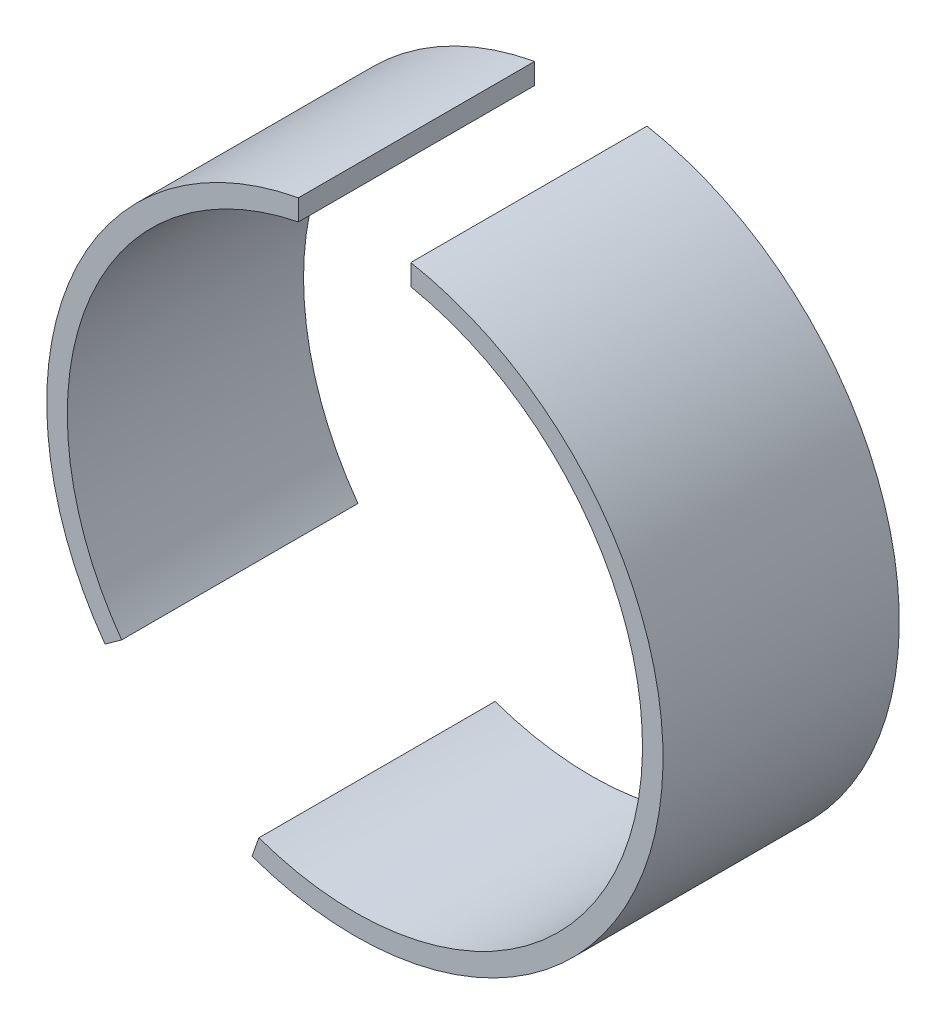
SolidWorks part; units mm, degrees
ref_plane "Front Plane" through (0, 0, 0) normal (0, 0, 1) x (1, 0, 0)
ref_plane "Top Plane" through (0, 0, 0) normal (0, 1, 0) x (1, 0, 0)
ref_plane "Right Plane" through (0, 0, 0) normal (1, 0, 0) x (0, 0, -1)
sketch "Sketch2" plane through (0, 0, 0) normal (0, 0, 1) x (1, 0, 0)
  line L0 (-9.3464, -26.394) -> (-10.014, -28.2793)
  line L1 (5.44, 27.4665) -> (5.44, 29.5027)
  line L7 (-24.3262, -17.5566) -> (-22.7045, -16.3862)
  line L8 (-5.5, 29.4915) -> (-5.5, 27.4545)
  arc A2 (-9.3464, -26.394) -> (5.44, 27.4665) centre (0, 0) ccw
  arc A5 (-5.5, 27.4545) -> (-22.7045, -16.3862) centre (0, 0) ccw
  arc A6 (-10.014, -28.2793) -> (5.44, 29.5027) centre (0, 0) ccw
  arc A7 (-5.5, 29.4915) -> (-24.3262, -17.5566) centre (0, 0) ccw
extrude "Boss-Extrude2" add sketch "Sketch2" along normal blind 23
